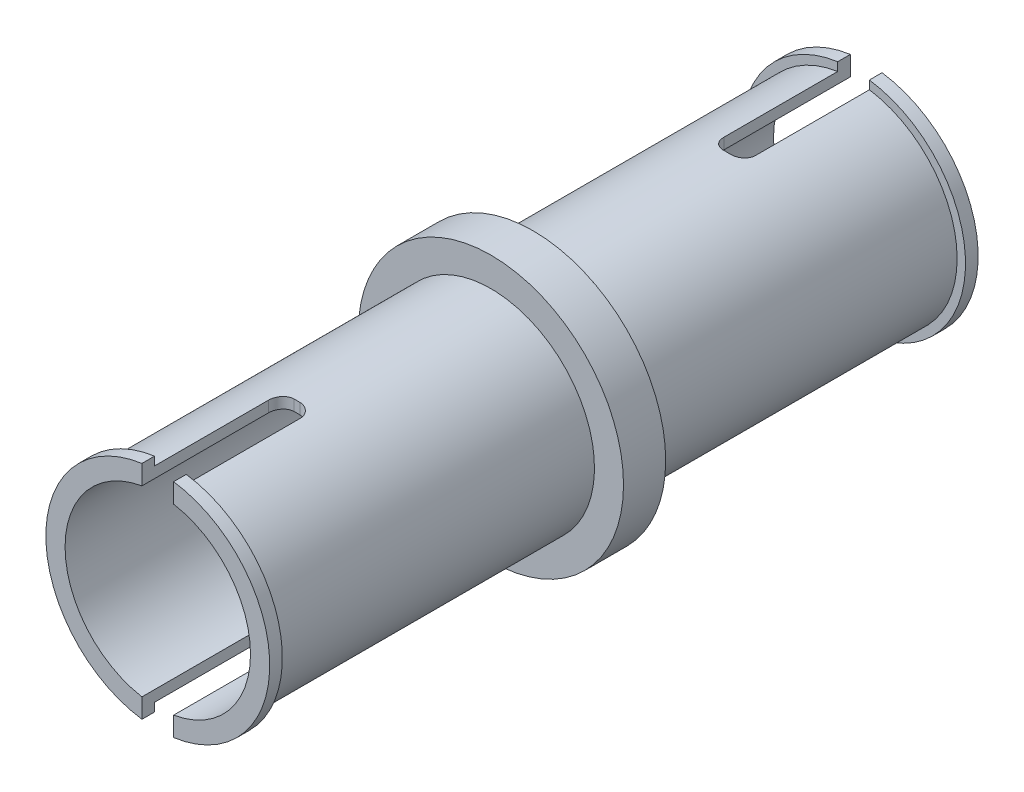
SolidWorks part; units mm, degrees
ref_plane "Front Plane" through (0, 0, 0) normal (0, 0, 1) x (1, 0, 0)
ref_plane "Top Plane" through (0, 0, 0) normal (0, 1, 0) x (1, 0, 0)
ref_plane "Right Plane" through (0, 0, 0) normal (1, 0, 0) x (0, 0, -1)
sketch "Sketch1" plane through (0, 0, 0) normal (0, 0, 1) x (1, 0, 0)
  line L0 (-2.4, 0) -> (2.4, 0)
  line L1 (-2.4, 0.895) -> (-2.4, -0.895)
  line L2 (-2.4, 0.895) -> (-0.9, 0.895)
  line L3 (0, 2.4) -> (0, -2.4)
  line L4 (-0.9, 0.895) -> (-0.9, 2.4)
  line L5 (-0.9, 2.4) -> (0.9, 2.4)
  line L6 (0.9, 0.895) -> (0.9, 2.4)
  line L7 (2.4, 0.895) -> (0.9, 0.895)
  line L8 (2.4, 0.895) -> (2.4, -0.895)
  line L9 (2.4, -0.895) -> (0.9, -0.895)
  line L10 (0.9, -0.895) -> (0.9, -2.4)
  line L11 (-0.9, -2.4) -> (0.9, -2.4)
  line L12 (-0.9, -0.895) -> (-0.9, -2.4)
  line L13 (-2.4, -0.895) -> (-0.9, -0.895)
  point P4 (0, 0)
  point P8 (-2.4, 0)
  point P12 (0, 0)
  dimension "D1" = 4.8
  dimension "D2" = 1.79
  dimension "D3" = 1.5
  dimension "D4" = 4.8
extrude "Boss-Extrude1" add sketch "Sketch1" along normal blind 7.9 contours L5 L4 L2 L1 L0 L3 | L1 L13 L12 L11 L3 L0 | L8 L7 L6 L5 L3 L0 | L3 L11 L10 L9 L8 L0
sketch "Sketch2" plane through (0, 0, 0) normal (0, 0, -1) x (-1, 0, 0)
  circle A0 centre (0, 0) radius 3.1445
extrude "Boss-Extrude3" add sketch "Sketch2" along normal blind 0.5 contours A0
sketch "Sketch3" plane through (0, 0, -0.5) normal (0, 0, -1) x (-1, 0, 0)
  circle A0 centre (0, 0) radius 2.4559
  dimension "D1" = 4.9118
extrude "Boss-Extrude4" add sketch "Sketch3" along normal blind 7.9
sketch "Sketch4" plane through (0, 0, -8.4) normal (0, 0, -1) x (-1, 0, 0)
  circle A0 centre (0, 0) radius 2.6546
extrude "Boss-Extrude5" add sketch "Sketch4" against normal blind 0.3
sketch "Sketch5" plane through (0, 0, -8.4) normal (0, 0, -1) x (-1, 0, 0)
  circle A0 centre (0, 0) radius 2.1986
extrude "Cut-Extrude1" cut sketch "Sketch5" against normal up to surface (7.9 mm away) up to face at (-2.4559, 0, -0.5)
sketch "Sketch6" plane through (0, 0, -8.4) normal (0, 0, -1) x (-1, 0, 0)
  line L0 (0, 0) -> (2.6546, 0) construction
  line L1 (0, 0) -> (0, 2.6546) construction
  line L2 (0.3755, 2.6546) -> (0.3755, 2.1663)
  line L3 (0.3755, 2.6546) -> (-0.3755, 2.6546)
  line L4 (0, 2.6546) -> (0, 2.1663)
  line L5 (0.3755, 2.1663) -> (-0.3755, 2.1663)
  line L6 (-0.3755, 2.6546) -> (-0.3755, 2.1663)
  line L7 (0.3755, -2.6546) -> (0.3755, -2.1663)
  line L8 (0.3755, -2.6546) -> (-0.3755, -2.6546)
  line L9 (-0.3755, -2.6546) -> (-0.3755, -2.1663)
  line L10 (0.3755, -2.1663) -> (-0.3755, -2.1663)
  circle A0 centre (0, 0) radius 2.6546 construction
  circle A1 centre (0, 0) radius 2.1986 construction
  circle M8 centre (0, 0) radius 2.1986
  circle M9 centre (0, 0) radius 2.6546
extrude "Cut-Extrude2" cut sketch "Sketch6" against normal blind 3.3 contours L4 L2 M9 M8 | L6 L4 M9 M8 | L9 L7 M9 M8
fillet "Fillet1" radius 0.3 4 edges at (-0.3755, -2.2967, -5.1) (0.3755, -2.2967, -5.1) (-0.3755, 2.2967, -5.1) (0.3755, 2.2967, -5.1)
sketch "Sketch7" plane through (0, 0, 0) normal (0, 0, 1) x (1, 0, 0)
  circle A0 centre (0, 0) radius 3.1445
extrude "Cut-Extrude5" cut sketch "Sketch7" along normal blind 9
mirror "Mirror3" of bodies 112
